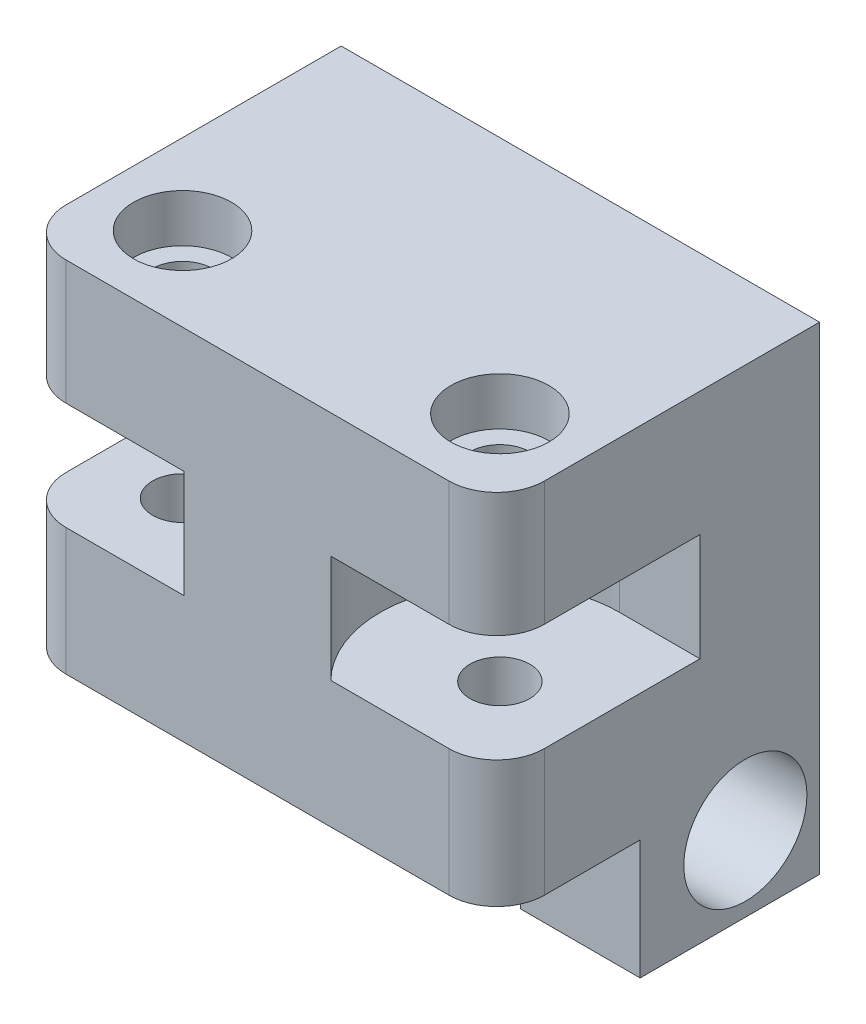
SolidWorks part; units mm, degrees
ref_plane "Front Plane" through (0, 0, 0) normal (0, 0, 1) x (1, 0, 0)
ref_plane "Top Plane" through (0, 0, 0) normal (0, 1, 0) x (1, 0, 0)
ref_plane "Right Plane" through (0, 0, 0) normal (1, 0, 0) x (0, 0, -1)
sketch "Sketch1" plane through (0, 0, 0) normal (0, 1, 0) x (1, 0, 0)
  line L1 (-22.8462, -9.1868) -> (17.1538, -9.1868)
  line L2 (-22.8462, -9.1868) -> (-22.8462, 17.8132)
  line L3 (-22.8462, 17.8132) -> (17.1538, 17.8132)
  line L4 (17.1538, -9.1868) -> (17.1538, 17.8132)
  dimension "D1" = 27
  dimension "D2" = 40
extrude "Boss-Extrude1" add sketch "Sketch1" along normal blind 30
sketch "Sketch2" plane through (0, 0, -17.8132) normal (0, 0, -1) x (-1, 0, 0)
  line L0 (2.8462, 30) -> (2.8462, 0) construction
  line L1 (-8.0864, 4) -> (-0.2064, 4)
  line L2 (-0.2064, 4) -> (-0.2064, 7)
  line L3 (-0.2064, 7) -> (-2.8664, 7)
  line L4 (-2.8664, 7) -> (-2.8664, 8.0087)
  line L5 (-2.8664, 8.0087) -> (-0.2538, 10.6287)
  line L6 (-0.2538, 10.6287) -> (5.9462, 10.6287)
  line L7 (-17.1538, 30) -> (22.8462, 30) construction
  line L8 (-17.1538, 0) -> (22.8462, 0) construction
  line L9 (-8.0864, 4) -> (-8.0864, 26)
  line L10 (-8.0864, 26) -> (-0.2064, 26)
  line L11 (-0.2064, 26) -> (-0.2064, 23)
  line L12 (-0.2064, 23) -> (-2.8664, 23)
  line L13 (-2.8664, 23) -> (-2.8664, 21.9913)
  line L14 (-2.8664, 21.9913) -> (-0.2464, 19.3787)
  line L15 (-0.2464, 19.3787) -> (5.9536, 19.3787)
  line L16 (-17.1538, 15) -> (22.8462, 15) construction
  line L17 (-17.1538, 30) -> (-17.1538, 0) construction
  line L18 (22.8462, 30) -> (22.8462, 0) construction
  line L19 (5.9387, 19.3787) -> (-0.2613, 19.3787)
  line L20 (8.5587, 21.9913) -> (5.9387, 19.3787)
  line L21 (8.5587, 23) -> (8.5587, 21.9913)
  line L22 (5.8987, 23) -> (8.5587, 23)
  line L23 (5.8987, 26) -> (5.8987, 23)
  line L24 (13.7787, 26) -> (5.8987, 26)
  line L25 (13.7787, 4) -> (13.7787, 26)
  line L26 (8.5587, 8.0087) -> (5.9462, 10.6287)
  line L27 (8.5587, 7) -> (8.5587, 8.0087)
  line L28 (5.8987, 7) -> (8.5587, 7)
  line L29 (5.8987, 4) -> (5.8987, 7)
  line L30 (13.7787, 4) -> (5.8987, 4)
  point P26 (-8.0864, 15)
  point P27 (2.8462, 15)
  point P37 (2.8462, 10.6287)
  dimension "D1" = 6.2
  dimension "D2" = 2.62
  dimension "D3" = 3.7
  dimension "D4" = 8.75
  dimension "D5" = 7.88
  dimension "D6" = 22
  dimension "D7" = 5.22
  dimension "D8" = 3
  dimension "D9" = 90
extrude "Cut-Extrude1" cut sketch "Sketch2" against normal blind 10
sketch "Sketch3" plane through (0, 0, 0) normal (0, -1, 0) x (1, 0, 0)
  line L0 (-22.8462, 9.1868) -> (17.1538, 9.1868) construction
  line L1 (17.1538, 9.1868) -> (17.1538, -17.8132) construction
  line L2 (-2.8462, 9.1868) -> (-2.8462, -17.8132) construction
  line L3 (17.1538, -17.8132) -> (-22.8462, -17.8132) construction
  circle A0 centre (10.4238, 2.1868) radius 2.5
  circle A2 centre (-16.1162, 2.1868) radius 2.5
  dimension "D1" = 5
  dimension "D3" = 7
  dimension "D4" = 6.73
extrude "Cut-Extrude2" cut sketch "Sketch3" against normal blind 30
sketch "Sketch8" plane through (0, 0, 0) normal (0, -1, 0) x (1, 0, 0)
  line L0 (3.2824, 9.1868) -> (17.1538, 9.1868)
  line L1 (-22.8462, 9.1868) -> (17.1538, 9.1868) construction
  line L2 (17.1538, 9.1868) -> (17.1538, -7.8132)
  line L3 (17.1538, 9.1868) -> (17.1538, -17.8132) construction
  line L4 (17.1538, -7.8132) -> (10.4238, -7.8132)
  line L6 (-2.8462, -17.8132) -> (-2.8462, 9.1868) construction
  line L7 (17.1538, -17.8132) -> (-22.8462, -17.8132) construction
  line L8 (-22.8462, -7.8132) -> (-16.1162, -7.8132)
  line L9 (-22.8462, 9.1868) -> (-22.8462, -7.8132)
  line L10 (-8.9747, 9.1868) -> (-22.8462, 9.1868)
  arc A0 (10.4238, -7.8132) -> (3.2824, 9.1868) centre (10.4238, 2.1868) cw
  arc A1 (-16.1162, -7.8132) -> (-8.9747, 9.1868) centre (-16.1162, 2.1868) ccw
  dimension "D1" = 10
extrude "Cut-Extrude5" cut sketch "Sketch8" against normal blind 9 from offset 10.62 offset against normal yes
sketch "Sketch10" plane through (8.0864, 0, 0) normal (-1, 0, 0) x (0, 0, 1)
  line L0 (-17.8132, 30) -> (-17.8132, 0) construction
  line L1 (-17.8132, 19.62) -> (2.1868, 19.62)
  line L2 (-17.8132, 19.62) -> (-17.8132, 10.62)
  line L3 (-17.8132, 10.62) -> (2.1868, 10.62)
  line L4 (2.1868, 19.62) -> (2.1868, 10.62)
  line L6 (9.1868, 19.62) -> (-7.8132, 19.62) construction
  line L7 (9.1868, 10.62) -> (-7.8132, 10.62) construction
  dimension "D1" = 20
extrude "Cut-Extrude7" cut sketch "Sketch10" along normal blind 6.8
sketch "Sketch12" plane through (-13.7787, 0, 0) normal (1, 0, 0) x (0, 0, -1)
  line L0 (-9.1868, 19.62) -> (1.8761, 19.62) construction
  line L1 (17.8132, 19.62) -> (-2.1868, 19.62)
  line L2 (17.8132, 19.62) -> (17.8132, 10.62)
  line L3 (17.8132, 10.62) -> (-2.1868, 10.62)
  line L4 (-2.1868, 19.62) -> (-2.1868, 10.62)
  line L6 (7.8132, 10.62) -> (-9.1868, 10.62) construction
  line L7 (17.8132, 30) -> (17.8132, 0) construction
  dimension "D1" = 20
extrude "Cut-Extrude10" cut sketch "Sketch12" along normal blind 6.8
fillet "Fillet1" radius 4 4 edges at (17.1538, 5.31, 9.1868) (17.1538, 24.81, 9.1868) (-22.8462, 5.31, 9.1868) (-22.8462, 24.81, 9.1868)
sketch "Sketch13" plane through (17.1538, 0, 0) normal (1, 0, 0) x (0, 0, -1)
  line L0 (-5.1868, 0) -> (17.8132, 0) construction
  line L1 (17.8132, 30) -> (17.8132, 0) construction
  line L3 (17.8132, 0) -> (2.8132, 0)
  line L4 (17.8132, 0) -> (17.8132, -10)
  line L5 (17.8132, -10) -> (2.8132, -10)
  line L6 (2.8132, 0) -> (2.8132, -10)
  circle A0 centre (11.6132, -3.7) radius 5.15
  line M3 (-5.1868, 0) -> (17.8132, 0)
  dimension "D1" = 6.2
  dimension "D2" = 3.7
  dimension "D3" = 10.3
  dimension "D4" = 15
  dimension "D5" = 10
extrude "Boss-Extrude2" add sketch "Sketch13" against normal up to surface (40 mm away) contours A0 L6 L5 L4 M3 up to face at (-22.8462, 15.06, -3.8132)
sketch "Sketch17" plane through (17.1538, 0, 0) normal (1, 0, 0) x (0, 0, -1)
  arc A3 (8.0309, 0) -> (15.1954, 0) centre (11.6132, -3.7) ccw construction
  arc A4 (8.0309, 0) -> (15.1954, 0) centre (11.6132, -3.7) ccw
  circle A5 centre (11.6132, -3.7) radius 5.15
extrude "Cut-Extrude14" cut sketch "Sketch17" against normal through all both and the other way through all contours A5
sketch "Sketch14" plane through (0, 0, -2.8132) normal (0, 0, 1) x (1, 0, 0)
  line L0 (-22.8462, -10) -> (17.1538, -10) construction
  line L1 (-12.8462, -10) -> (7.1538, -10)
  line L2 (-12.8462, -10) -> (-12.8462, 0)
  line L3 (-12.8462, 0) -> (7.1538, 0)
  line L4 (7.1538, -10) -> (7.1538, 0)
  line L5 (-18.8462, 0) -> (13.1538, 0) construction
  dimension "D1" = 20
extrude "Cut-Extrude11" cut sketch "Sketch14" against normal up to next
sketch "Sketch15" plane through (0, 30, 0) normal (0, 1, 0) x (1, 0, 0)
  line L0 (-2.8462, 17.8132) -> (-2.8462, -9.1868) construction
  line L13 (17.1538, 17.8132) -> (-22.8462, 17.8132) construction
  line L14 (-18.8462, -9.1868) -> (13.1538, -9.1868) construction
  circle A4 centre (-16.1162, -2.1868) radius 4.1
  circle A5 centre (10.4238, -2.1868) radius 4.1
  dimension "D1" = 8.2
extrude "Cut-Extrude12" cut sketch "Sketch15" against normal blind 4
sketch "Sketch16" plane through (0, 0, 0) normal (0, -1, 0) x (1, 0, 0)
  line L1 (-13.749, -1.9132) -> (-11.3819, 2.1868)
  line L2 (-11.3819, 2.1868) -> (-13.749, 6.2868)
  line L3 (-13.749, 6.2868) -> (-18.4833, 6.2868)
  line L4 (-18.4833, 6.2868) -> (-20.8504, 2.1868)
  line L5 (-20.8504, 2.1868) -> (-18.4833, -1.9132)
  line L6 (-18.4833, -1.9132) -> (-13.749, -1.9132)
  line L7 (12.791, -1.9132) -> (15.1581, 2.1868)
  line L8 (15.1581, 2.1868) -> (12.791, 6.2868)
  line L9 (12.791, 6.2868) -> (8.0567, 6.2868)
  line L10 (8.0567, 6.2868) -> (5.6896, 2.1868)
  line L11 (5.6896, 2.1868) -> (8.0567, -1.9132)
  line L12 (8.0567, -1.9132) -> (12.791, -1.9132)
  circle A0 centre (10.4238, 2.1868) radius 2.5 construction
  circle A1 centre (-16.1162, 2.1868) radius 2.5 construction
  circle A2 centre (10.4238, 2.1868) radius 2.5
  circle A3 centre (-16.1162, 2.1868) radius 2.5
  circle A4 centre (-16.1162, 2.1868) radius 4.1 construction
  circle A5 centre (10.4238, 2.1868) radius 4.1 construction
  dimension "D1" = 8.2
  dimension "D2" = 8.2
extrude "Cut-Extrude13" cut sketch "Sketch16" against normal blind 4
